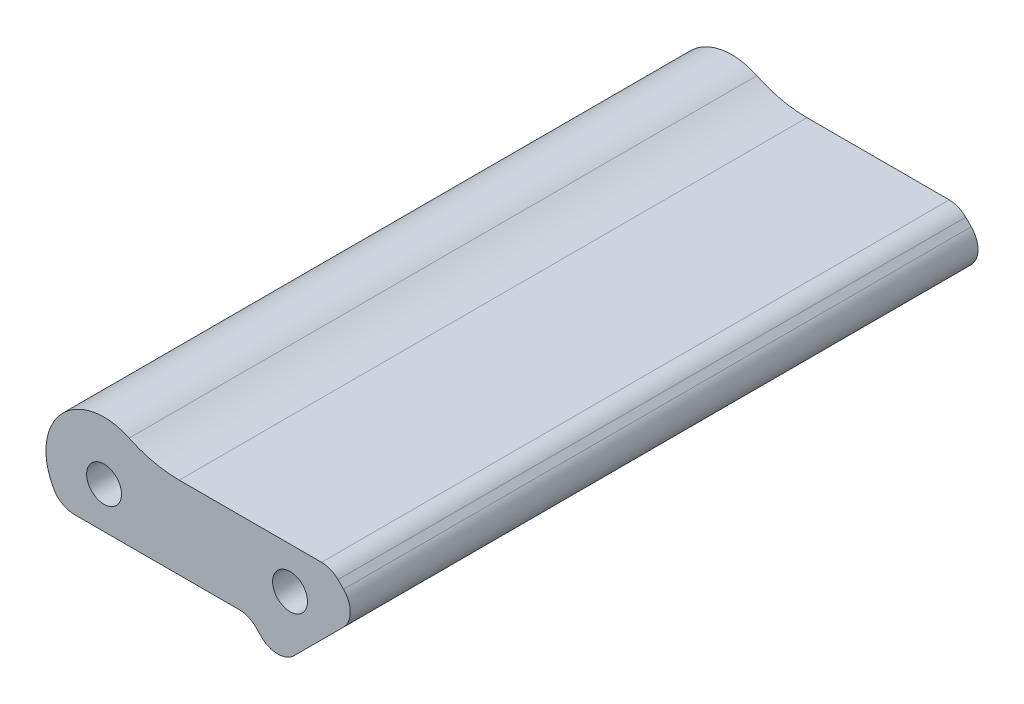
SolidWorks part; units mm, degrees
ref_plane "前视基准面" through (0, 0, 0) normal (0, 0, 1) x (1, 0, 0)
ref_plane "上视基准面" through (0, 0, 0) normal (0, 1, 0) x (1, 0, 0)
ref_plane "右视基准面" through (0, 0, 0) normal (1, 0, 0) x (0, 0, -1)
other "Configuration Table"
sketch "草图1" plane through (0, 0, 0) normal (0, 0, 1) x (1, 0, 0)
  line L0 (-8, 0) -> (8, 0) construction
  line L1 (15.3912, 2.4415) -> (-35339.9478, -35352.8976) construction
  line L6 (-8, 0) -> (35347.3391, 35355.3391) construction
  line L7 (8, 0) -> (-35347.3391, -35355.3391) construction
  line L8 (-10.5772, -3.5355) -> (3.636, -3.5355)
  line L9 (5.0503, -4.1213) -> (5.5251, -4.5962)
  line L10 (8.3536, -4.5962) -> (12.5962, -0.3536)
  line L11 (12.5962, 2.4749) -> (12.1213, 2.9497)
  line L12 (10.7071, 3.5355) -> (-1.5355, 3.5355)
  line L13 (8, 0) -> (35363.3391, -35355.3391) construction
  circle A0 centre (-8, 0) radius 1.5
  circle A1 centre (8, 0) radius 1.5
  arc A2 (-5.8452, 4.5118) -> (-12.2954, -2.5592) centre (-8, 0) ccw
  arc A3 (-1.5355, 3.5355) -> (-5.8452, 4.5118) centre (-1.5355, 13.5355) cw
  arc A4 (12.1213, 2.9497) -> (10.7071, 3.5355) centre (10.7071, 1.5355) ccw
  arc A5 (3.636, -3.5355) -> (5.0503, -4.1213) centre (3.636, -5.5355) cw
  arc A6 (-10.5772, -3.5355) -> (-12.2954, -2.5592) centre (-10.5772, -1.5355) cw
  arc A7 (5.5251, -4.5962) -> (8.3536, -4.5962) centre (6.9393, -3.182) ccw
  arc A8 (12.5962, -0.3536) -> (12.5962, 2.4749) centre (11.182, 1.0607) ccw
  point P4 (0, 0)
  point P7 (0, 0)
  point P24 (-4.4645, 3.5355)
  point P26 (11.5355, 3.5355)
  point P29 (4.4645, -3.5355)
  point P32 (-11.5355, -3.5355)
  point P35 (6.9393, -6.0104)
  point P38 (14.0104, 1.0607)
  dimension "D1" = 3
  dimension "D6" = 10
  dimension "D7" = 2
  dimension "D8" = 2
  dimension "D2" = 16
  dimension "D3" = 45
  dimension "D4" = 3.5
  dimension "D5" = 10
extrude "凸台-拉伸1" add sketch "草图1" along normal blind 54
